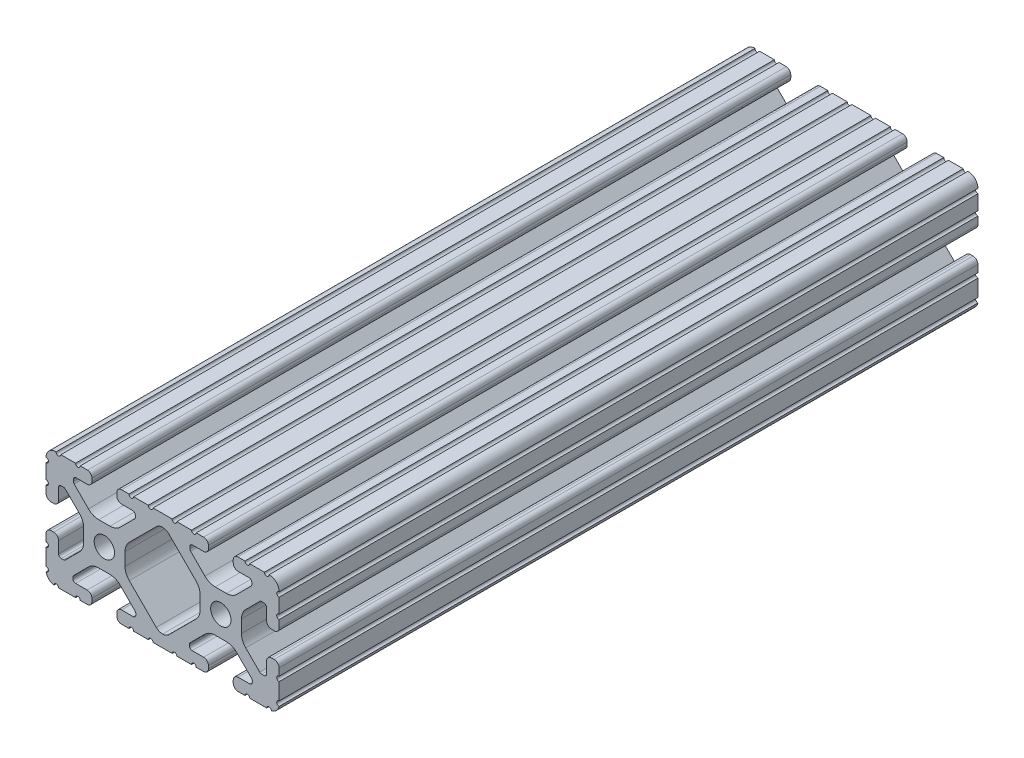
SolidWorks part; units mm, degrees
material "6005A-T61"
ref_plane "Front Plane" through (0, 0, 0) normal (0, 0, 1) x (1, 0, 0)
ref_plane "Top Plane" through (0, 0, 0) normal (0, 1, 0) x (1, 0, 0)
ref_plane "Right Plane" through (0, 0, 0) normal (1, 0, 0) x (0, 0, -1)
sketch "Sketch1" plane through (0, 0, 0) normal (0, 0, 1) x (1, 0, 0)
  line L0 (-3.1211, -19.05) -> (3.1211, -19.05)
  line L1 (-38.1, 10.287) -> (-38.1, 14.3752)
  line L2 (0, -34.5561) -> (0, 32.8014) construction
  line L3 (-38.1, 0) -> (0, 0) construction
  line L4 (-38.1, 9.5497) -> (-38.1, 10.287)
  line L5 (-19.05, 19.05) -> (-19.05, -20.2827) construction
  line L6 (0, -15.1247) -> (0, -15.1131) construction
  line L7 (9.1761, 12.9058) -> (13.8525, 8.2294)
  line L8 (8.9158, 14.097) -> (8.9158, 13.5344)
  line L9 (13.4112, 14.986) -> (9.8048, 14.986)
  line L10 (14.986, 17.4968) -> (14.986, 16.5608)
  line L11 (10.9975, 19.05) -> (13.4328, 19.05)
  line L12 (8.6331, 19.05) -> (9.4735, 19.05)
  line L13 (4.6451, 19.05) -> (8.6331, 19.05)
  line L14 (31.792, 10.0266) -> (27.1976, 5.4321)
  line L15 (33.147, 10.287) -> (32.4207, 10.287)
  line L16 (29.2071, 19.05) -> (33.2963, 19.05)
  line L17 (28.4698, 19.05) -> (29.2071, 19.05)
  line L18 (-38.1, 5.6388) -> (-38.1, 8.0257)
  line L19 (24.5589, 19.05) -> (26.9458, 19.05)
  line L20 (23.114, 16.5608) -> (23.114, 17.4806)
  line L21 (28.2952, 14.986) -> (24.6888, 14.986)
  line L22 (29.1842, 13.5344) -> (29.1842, 14.097)
  line L23 (-34.036, 9.398) -> (-34.036, 5.6388)
  line L24 (-35.6108, 4.064) -> (-36.5252, 4.064)
  line L25 (24.2475, 8.2294) -> (28.9239, 12.9058)
  line L26 (25.8064, -2.0735) -> (25.8064, 2.0735)
  line L27 (35.6108, 4.064) -> (36.5252, 4.064)
  line L28 (34.036, 9.398) -> (34.036, 5.6388)
  line L29 (38.1, 5.6388) -> (38.1, 8.0257)
  line L30 (38.1, 9.5497) -> (38.1, 10.287)
  line L31 (38.1, 10.287) -> (38.1, 14.3752)
  line L32 (17.2111, 6.8382) -> (20.8889, 6.8382)
  line L33 (2.077, 14.2576) -> (10.9024, 5.4321)
  line L34 (-31.792, -10.0266) -> (-27.1976, -5.4321)
  line L35 (-33.147, -10.287) -> (-32.4207, -10.287)
  line L36 (-29.2071, -19.05) -> (-34.0473, -19.05)
  line L37 (-28.4698, -19.05) -> (-29.2071, -19.05)
  line L38 (-24.6888, -19.05) -> (-26.9458, -19.05)
  line L39 (12.2936, -2.0735) -> (12.2936, 2.0735)
  line L40 (-23.114, -16.5608) -> (-23.114, -17.4752)
  line L41 (-28.448, -14.986) -> (-24.6888, -14.986)
  line L42 (-29.337, -13.6872) -> (-29.337, -14.097)
  line L43 (2.077, -14.2576) -> (10.9024, -5.4321)
  line L44 (-3.1211, 19.05) -> (3.1211, 19.05)
  line L45 (8.763, -14.097) -> (8.763, -13.6872)
  line L46 (-24.2475, -8.2294) -> (-29.0766, -13.0586)
  line L47 (-35.6108, -4.064) -> (-36.5252, -4.064)
  line L48 (-34.036, -9.398) -> (-34.036, -5.6388)
  line L49 (-38.1, -5.6388) -> (-38.1, -8.0257)
  line L50 (-38.1, -9.5497) -> (-38.1, -10.287)
  line L51 (-38.1, -10.287) -> (-38.1, -15.036)
  line L52 (17.2111, -6.8382) -> (20.8889, -6.8382)
  line L53 (38.1, -10.287) -> (38.1, -15.036)
  line L54 (38.1, -9.5497) -> (38.1, -10.287)
  line L55 (38.1, -5.6388) -> (38.1, -8.0257)
  line L56 (34.036, -9.398) -> (34.036, -5.6388)
  line L57 (35.6108, -4.064) -> (36.5252, -4.064)
  line L58 (24.2475, -8.2294) -> (29.0766, -13.0586)
  line L59 (29.337, -13.6872) -> (29.337, -14.097)
  line L60 (-17.2111, -6.8382) -> (-20.8889, -6.8382)
  line L61 (-9.0234, -13.0586) -> (-13.8525, -8.2294)
  line L62 (-8.763, -14.097) -> (-8.763, -13.6872)
  line L63 (-13.4112, -14.986) -> (-9.652, -14.986)
  line L64 (-14.986, -17.4752) -> (-14.986, -16.5608)
  line L65 (-10.9975, -19.05) -> (-13.4112, -19.05)
  line L66 (28.448, -14.986) -> (24.6888, -14.986)
  line L67 (23.114, -16.5608) -> (23.114, -17.4752)
  line L68 (24.6888, -19.05) -> (26.9458, -19.05)
  line L69 (28.4698, -19.05) -> (29.2071, -19.05)
  line L70 (29.2071, -19.05) -> (34.0473, -19.05)
  line L71 (-8.6331, -19.05) -> (-9.4735, -19.05)
  line L72 (33.147, -10.287) -> (32.4207, -10.287)
  line L73 (31.792, -10.0266) -> (27.1976, -5.4321)
  line L74 (-4.6451, -19.05) -> (-8.6331, -19.05)
  line L75 (9.0234, -13.0586) -> (13.8525, -8.2294)
  line L76 (13.4112, -14.986) -> (9.652, -14.986)
  line L77 (-2.077, -14.2576) -> (-10.9024, -5.4321)
  line L78 (14.986, -17.4752) -> (14.986, -16.5608)
  line L79 (10.9975, -19.05) -> (13.4112, -19.05)
  line L80 (4.6451, -19.05) -> (8.6331, -19.05)
  line L81 (8.6331, -19.05) -> (9.4735, -19.05)
  line L83 (-12.2936, -2.0735) -> (-12.2936, 2.0735)
  line L84 (-25.8064, -2.0735) -> (-25.8064, 2.0735)
  line L85 (-2.077, 14.2576) -> (-10.9024, 5.4321)
  line L87 (-4.6451, 19.05) -> (-8.6331, 19.05)
  line L88 (-8.6331, 19.05) -> (-9.4735, 19.05)
  line L89 (-10.9975, 19.05) -> (-13.4328, 19.05)
  line L90 (-14.986, 17.4968) -> (-14.986, 16.5608)
  line L91 (-13.4112, 14.986) -> (-9.8048, 14.986)
  line L92 (-8.9158, 14.097) -> (-8.9158, 13.5344)
  line L93 (-9.1761, 12.9058) -> (-13.8525, 8.2294)
  line L94 (-17.2111, 6.8382) -> (-20.8889, 6.8382)
  line L95 (-24.2475, 8.2294) -> (-28.9239, 12.9058)
  line L96 (-29.1842, 13.5344) -> (-29.1842, 14.097)
  line L97 (-28.2952, 14.986) -> (-24.6888, 14.986)
  line L98 (-23.114, 16.5608) -> (-23.114, 17.4806)
  line L99 (-24.5589, 19.05) -> (-26.9458, 19.05)
  line L100 (-28.4698, 19.05) -> (-29.2071, 19.05)
  line L101 (-29.2071, 19.05) -> (-33.2963, 19.05)
  line L109 (-33.147, 10.287) -> (-32.4207, 10.287)
  line L165 (-31.792, 10.0266) -> (-27.1976, 5.4321)
  arc A0 (-38.1376, 15.8983) -> (-38.1, 14.3752) centre (-38.1, 15.1372) cw
  arc A1 (-38.1, 9.5497) -> (-38.1, 8.0257) centre (-38.1, 8.7877) cw
  arc A2 (9.1761, 12.9058) -> (8.9158, 13.5344) centre (9.8048, 13.5344) cw
  arc A3 (8.9158, 14.097) -> (9.8048, 14.986) centre (9.8048, 14.097) cw
  arc A4 (-36.5252, 4.064) -> (-38.1, 5.6388) centre (-36.5252, 5.6388) cw
  arc A5 (14.986, 16.5608) -> (13.4112, 14.986) centre (13.4112, 16.5608) cw
  arc A6 (13.4328, 19.05) -> (14.986, 17.4968) centre (13.4328, 17.4968) cw
  arc A7 (10.9975, 19.05) -> (9.4735, 19.05) centre (10.2355, 19.05) cw
  arc A8 (4.6451, 19.05) -> (3.1211, 19.05) centre (3.8831, 19.05) cw
  arc A9 (0, 15.1131) -> (2.077, 14.2576) centre (0.0116, 12.1921) cw
  arc A10 (25.8064, 2.0735) -> (27.1976, 5.4321) centre (30.5562, 2.0735) cw
  arc A11 (31.792, 10.0266) -> (32.4207, 10.287) centre (32.4207, 9.398) cw
  arc A12 (33.147, 10.287) -> (34.036, 9.398) centre (33.147, 9.398) cw
  arc A13 (34.8195, 19.0968) -> (38.1376, 15.8983) centre (34.903, 15.8631) cw
  arc A14 (34.8195, 19.0968) -> (33.2963, 19.05) centre (34.0579, 19.0734) cw
  arc A15 (28.4698, 19.05) -> (26.9458, 19.05) centre (27.7078, 19.05) cw
  arc A16 (23.114, 17.4806) -> (24.5589, 19.05) centre (24.6888, 17.4806) cw
  arc A17 (24.6888, 14.986) -> (23.114, 16.5608) centre (24.6888, 16.5608) cw
  arc A18 (28.2952, 14.986) -> (29.1842, 14.097) centre (28.2952, 14.097) cw
  arc A19 (29.1842, 13.5344) -> (28.9239, 12.9058) centre (28.2952, 13.5344) cw
  arc A20 (-35.5713, -19.05) -> (-38.1, -16.56) centre (-34.9455, -15.8855) cw
  arc A21 (34.036, 5.6388) -> (35.6108, 4.064) centre (35.6108, 5.6388) ccw
  arc A22 (36.5252, 4.064) -> (38.1, 5.6388) centre (36.5252, 5.6388) ccw
  arc A23 (38.1, 9.5497) -> (38.1, 8.0257) centre (38.1, 8.7877) ccw
  arc A24 (24.2475, 8.2294) -> (20.8889, 6.8382) centre (20.8889, 11.588) cw
  arc A25 (17.2111, 6.8382) -> (13.8525, 8.2294) centre (17.2111, 11.588) cw
  arc A26 (10.9024, 5.4321) -> (12.2936, 2.0735) centre (7.5438, 2.0735) cw
  arc A27 (0, -15.1131) -> (2.077, -14.2576) centre (0.0116, -12.1921) ccw
  arc A28 (-34.036, 5.6388) -> (-35.6108, 4.064) centre (-35.6108, 5.6388) cw
  arc A29 (-25.8064, -2.0735) -> (-27.1976, -5.4321) centre (-30.5562, -2.0735) cw
  arc A30 (-31.792, -10.0266) -> (-32.4207, -10.287) centre (-32.4207, -9.398) cw
  arc A31 (-33.147, -10.287) -> (-34.036, -9.398) centre (-33.147, -9.398) cw
  arc A33 (-35.5713, -19.05) -> (-34.0473, -19.05) centre (-34.8093, -19.05) cw
  arc A34 (-28.4698, -19.05) -> (-26.9458, -19.05) centre (-27.7078, -19.05) cw
  arc A35 (10.9024, -5.4321) -> (12.2936, -2.0735) centre (7.5438, -2.0735) ccw
  circle A36 centre (19.05, 0) radius 3.3274
  arc A37 (-23.114, -17.4752) -> (-24.6888, -19.05) centre (-24.6888, -17.4752) cw
  arc A38 (-24.6888, -14.986) -> (-23.114, -16.5608) centre (-24.6888, -16.5608) cw
  arc A39 (-28.448, -14.986) -> (-29.337, -14.097) centre (-28.448, -14.097) cw
  arc A40 (-29.337, -13.6872) -> (-29.0766, -13.0586) centre (-28.448, -13.6872) cw
  arc A41 (-24.2475, -8.2294) -> (-20.8889, -6.8382) centre (-20.8889, -11.588) cw
  arc A42 (-34.036, -5.6388) -> (-35.6108, -4.064) centre (-35.6108, -5.6388) ccw
  arc A43 (-36.5252, -4.064) -> (-38.1, -5.6388) centre (-36.5252, -5.6388) ccw
  arc A44 (-38.1, -9.5497) -> (-38.1, -8.0257) centre (-38.1, -8.7877) ccw
  arc A45 (-38.1, -16.56) -> (-38.1, -15.036) centre (-38.1, -15.798) ccw
  arc A46 (38.1, -16.56) -> (38.1, -15.036) centre (38.1, -15.798) cw
  arc A47 (38.1, -9.5497) -> (38.1, -8.0257) centre (38.1, -8.7877) cw
  arc A48 (36.5252, -4.064) -> (38.1, -5.6388) centre (36.5252, -5.6388) cw
  arc A49 (34.036, -5.6388) -> (35.6108, -4.064) centre (35.6108, -5.6388) cw
  arc A50 (24.2475, -8.2294) -> (20.8889, -6.8382) centre (20.8889, -11.588) ccw
  arc A51 (29.337, -13.6872) -> (29.0766, -13.0586) centre (28.448, -13.6872) ccw
  arc A52 (28.448, -14.986) -> (29.337, -14.097) centre (28.448, -14.097) ccw
  arc A53 (24.6888, -14.986) -> (23.114, -16.5608) centre (24.6888, -16.5608) ccw
  arc A54 (-17.2111, -6.8382) -> (-13.8525, -8.2294) centre (-17.2111, -11.588) cw
  arc A55 (-9.0234, -13.0586) -> (-8.763, -13.6872) centre (-9.652, -13.6872) cw
  arc A56 (-8.763, -14.097) -> (-9.652, -14.986) centre (-9.652, -14.097) cw
  arc A57 (-14.986, -16.5608) -> (-13.4112, -14.986) centre (-13.4112, -16.5608) cw
  arc A58 (-13.4112, -19.05) -> (-14.986, -17.4752) centre (-13.4112, -17.4752) cw
  arc A59 (-10.9975, -19.05) -> (-9.4735, -19.05) centre (-10.2355, -19.05) cw
  arc A60 (-4.6451, -19.05) -> (-3.1211, -19.05) centre (-3.8831, -19.05) cw
  arc A61 (23.114, -17.4752) -> (24.6888, -19.05) centre (24.6888, -17.4752) ccw
  arc A62 (28.4698, -19.05) -> (26.9458, -19.05) centre (27.7078, -19.05) ccw
  arc A63 (35.5713, -19.05) -> (34.0473, -19.05) centre (34.8093, -19.05) ccw
  arc A64 (35.5713, -19.05) -> (38.1, -16.56) centre (34.9379, -15.8778) ccw
  arc A65 (33.147, -10.287) -> (34.036, -9.398) centre (33.147, -9.398) ccw
  arc A66 (31.792, -10.0266) -> (32.4207, -10.287) centre (32.4207, -9.398) ccw
  arc A67 (-10.9024, -5.4321) -> (-12.2936, -2.0735) centre (-7.5438, -2.0735) cw
  arc A68 (0, -15.1131) -> (-2.077, -14.2576) centre (-0.0116, -12.1921) cw
  arc A69 (0, 15.1131) -> (-2.077, 14.2576) centre (-0.0116, 12.1921) ccw
  arc A70 (-10.9024, 5.4321) -> (-12.2936, 2.0735) centre (-7.5438, 2.0735) ccw
  arc A71 (25.8064, -2.0735) -> (27.1976, -5.4321) centre (30.5562, -2.0735) ccw
  arc A72 (9.0234, -13.0586) -> (8.763, -13.6872) centre (9.652, -13.6872) ccw
  arc A73 (8.763, -14.097) -> (9.652, -14.986) centre (9.652, -14.097) ccw
  arc A74 (17.2111, -6.8382) -> (13.8525, -8.2294) centre (17.2111, -11.588) ccw
  arc A75 (13.4112, -19.05) -> (14.986, -17.4752) centre (13.4112, -17.4752) ccw
  arc A76 (14.986, -16.5608) -> (13.4112, -14.986) centre (13.4112, -16.5608) ccw
  arc A77 (-4.6451, 19.05) -> (-3.1211, 19.05) centre (-3.8831, 19.05) ccw
  arc A78 (-10.9975, 19.05) -> (-9.4735, 19.05) centre (-10.2355, 19.05) ccw
  arc A79 (-13.4328, 19.05) -> (-14.986, 17.4968) centre (-13.4328, 17.4968) ccw
  arc A80 (-14.986, 16.5608) -> (-13.4112, 14.986) centre (-13.4112, 16.5608) ccw
  arc A81 (-8.9158, 14.097) -> (-9.8048, 14.986) centre (-9.8048, 14.097) ccw
  arc A82 (-9.1761, 12.9058) -> (-8.9158, 13.5344) centre (-9.8048, 13.5344) ccw
  arc A83 (-17.2111, 6.8382) -> (-13.8525, 8.2294) centre (-17.2111, 11.588) ccw
  arc A84 (-24.2475, 8.2294) -> (-20.8889, 6.8382) centre (-20.8889, 11.588) ccw
  arc A85 (-29.1842, 13.5344) -> (-28.9239, 12.9058) centre (-28.2952, 13.5344) ccw
  arc A86 (-28.2952, 14.986) -> (-29.1842, 14.097) centre (-28.2952, 14.097) ccw
  arc A87 (-24.6888, 14.986) -> (-23.114, 16.5608) centre (-24.6888, 16.5608) ccw
  arc A88 (-23.114, 17.4806) -> (-24.5589, 19.05) centre (-24.6888, 17.4806) ccw
  arc A89 (-28.4698, 19.05) -> (-26.9458, 19.05) centre (-27.7078, 19.05) ccw
  arc A90 (-34.8195, 19.0968) -> (-33.2963, 19.05) centre (-34.0579, 19.0734) ccw
  arc A91 (-34.8195, 19.0968) -> (-38.1376, 15.8983) centre (-34.903, 15.8631) ccw
  arc A92 (4.6451, -19.05) -> (3.1211, -19.05) centre (3.8831, -19.05) ccw
  arc A93 (10.9975, -19.05) -> (9.4735, -19.05) centre (10.2355, -19.05) ccw
  arc A94 (38.1376, 15.8983) -> (38.1, 14.3752) centre (38.1, 15.1372) ccw
  arc A96 (-33.147, 10.287) -> (-34.036, 9.398) centre (-33.147, 9.398) ccw
  arc A97 (-31.792, 10.0266) -> (-32.4207, 10.287) centre (-32.4207, 9.398) ccw
  arc A98 (-25.8064, 2.0735) -> (-27.1976, 5.4321) centre (-30.5562, 2.0735) ccw
  circle A101 centre (-19.05, 0) radius 3.3274
  point P34 (0, 19.05)
  point P79 (25.6765, 0)
  point P274 (0, -19.05)
  point P282 (-25.6765, 0)
  point P283 (-12.2936, 0)
  dimension "D1" = 38.1
  dimension "D4" = 6.6548
  dimension "D10" = 4.064
  dimension "D2" = 76.2
  dimension "D3" = 38.1
  dimension "D5" = 8.128
  dimension "D6" = 20.574
  dimension "D7" = 12.2936
  dimension "D8" = 4.064
  dimension "D9" = 4.064
extrude "Extrude1" add sketch "Sketch1" against normal blind 228.6
